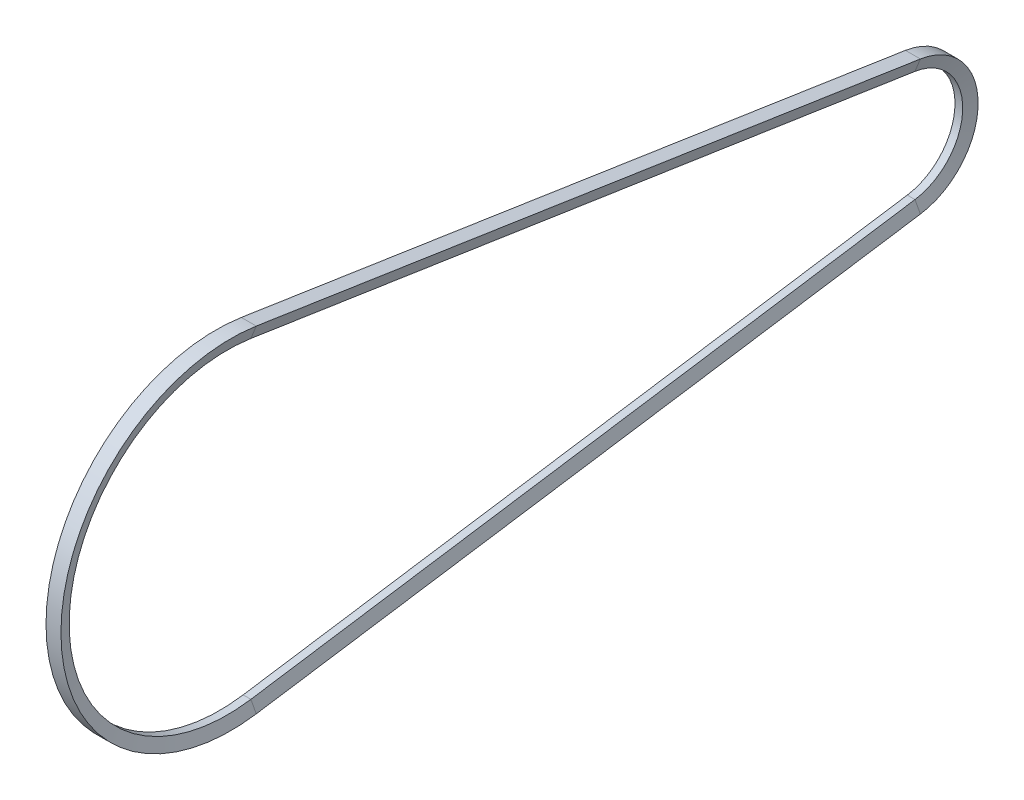
SolidWorks part; units mm, degrees
ref_plane "前视基准面" through (0, 0, 0) normal (0, 0, 1) x (1, 0, 0)
ref_plane "上视基准面" through (0, 0, 0) normal (0, 1, 0) x (1, 0, 0)
ref_plane "右视基准面" through (0, 0, 0) normal (1, 0, 0) x (0, 0, -1)
sketch "草图1" plane through (0, 0, 0) normal (1, 0, 0) x (0, 0, -1)
  line L0 (18.75, 123.5857) -> (507.5, 49.4343)
  line L1 (18.75, -123.5857) -> (507.5, -49.4343)
  line L2 (0, 0) -> (500, 0) construction
  arc A0 (18.75, 123.5857) -> (18.75, -123.5857) centre (0, 0) ccw
  arc A1 (507.5, -49.4343) -> (507.5, 49.4343) centre (500, 0) ccw
  dimension "D1" = 125
  dimension "D2" = 50
  dimension "D3" = 500
sketch "草图2" plane through (0, 0, 0) normal (0, 0, 1) x (1, 0, 0)
  line L0 (-5.5, 125) -> (5.5, 125)
  line L1 (5.5, 125) -> (2.8401, 116.3)
  line L2 (2.8401, 116.3) -> (-2.8401, 116.3)
  line L3 (-2.8401, 116.3) -> (-5.5, 125)
  line L4 (0, 116.3) -> (0, 125) construction
  line L5 (0, -125) -> (0, 125) construction
  dimension "D1" = 11
  dimension "D2" = 8.7
  dimension "D3" = 34
sweep "扫描1" add profiles "草图2" path "草图1"
equation "\"D3@草图1\" = \"D1@距离1@实心轮_实心轮.Assembly\""
equation "\"D1@草图2\" = \"bd@草图1@小带轮_实心轮.Part\" "
equation "\"D2@草图2\" = \"hf@草图1@小带轮_实心轮.Part\" "
equation "\"D3@草图2\" = \"槽轮角@草图1@小带轮_实心轮.Part\" "
equation "\"D2@草图1\" = \"dd@草图1@小带轮_实心轮.Part\"/2"
equation "\"D1@草图1\" = \"dd@草图1@大带轮_实心轮.Part\" /2"
